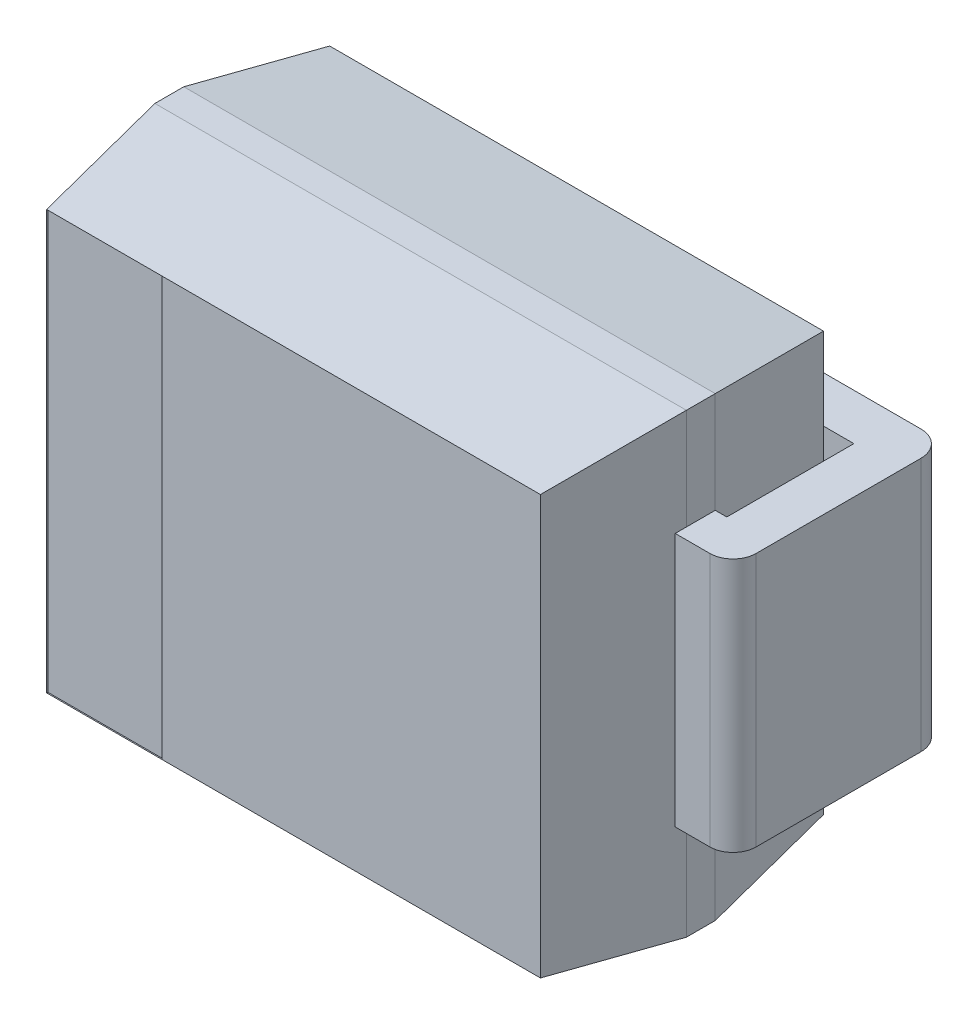
SolidWorks part; units mm, degrees
other "Детальный элемент1"
ref_plane "Спереди" through (0, 0, 0) normal (0, 0, 1) x (1, 0, 0)
ref_plane "Сверху" through (0, 0, 0) normal (0, 1, 0) x (1, 0, 0)
ref_plane "Справа" through (0, 0, 0) normal (1, 0, 0) x (0, 0, -1)
ref_plane "Плоскость1" through (0, 0, 0.4) normal (0, 0, 1) x (1, 0, 0)
sketch "Эскиз1" plane through (0, 0, 0.4) normal (0, 0, 1) x (1, 0, 0)
  line L1 (-2.3, 1.975) -> (2.3, 1.975)
  line L2 (-2.3, 1.975) -> (-2.3, -1.975)
  line L3 (-2.3, -1.975) -> (2.3, -1.975)
  line L4 (2.3, 1.975) -> (2.3, -1.975)
  line L5 (-2.3, 1.975) -> (2.3, -1.975) construction
  line L6 (-2.3, -1.975) -> (2.3, 1.975) construction
  point P0 (0, 0)
  dimension "D1" = 4.6
  dimension "D2" = 3.95
extrude "Бобышка-Вытянуть1" add sketch "Эскиз1" along normal blind 2.45
chamfer "Фаска1" distance 1.1 distance2 0.163 4 edges at (0, 1.975, 2.85) (2.3, 0, 2.85) (0, -1.975, 2.85) (-2.3, 0, 2.85)
chamfer "Фаска2" distance 0.163 distance2 1.1 4 edges at (2.3, 0, 0.4) (0, 1.975, 0.4) (0, -1.975, 0.4) (-2.3, 0, 0.4)
sketch "Эскиз2" plane through (0, 0, 0) normal (0, 1, 0) x (1, 0, 0)
  line L0 (-2.4, -0.4) -> (-2.4, -1.5)
  line L1 (-1.3, 0) -> (-2.58, 0)
  line L2 (-1.3, 0) -> (-1.3, -0.4)
  line L3 (-1.3, -0.4) -> (-2.4, -0.4)
  line L5 (-2.8, -1.6464) -> (-2.8, -0.22)
  line L6 (-2.6, -1.8464) -> (-2.3, -1.8464)
  line L7 (-2.3, -1.8464) -> (-2.3, -1.5)
  line L8 (-2.3, -1.5) -> (-2.4, -1.5)
  arc A2 (-2.6, -1.8464) -> (-2.8, -1.6464) centre (-2.6, -1.6464) cw
  arc A3 (-2.58, 0) -> (-2.8, -0.22) centre (-2.58, -0.22) ccw
  point P4 (0, 0)
  dimension "D3" = 0.22
  dimension "D6" = 0.2
  dimension "D1" = 0.4
  dimension "D2" = 0.4
  dimension "D4" = 1.5
  dimension "D5" = 0.5
extrude "Бобышка-Вытянуть2" add sketch "Эскиз2" along normal blind 1.1 and the other way blind 1.1 separate body
mirror "Зеркальное отражение1" about plane through (0, 0, 0) normal (1, 0, 0) of bodies 108
sketch "Эскиз3" plane through (0, 0, 2.85) normal (0, 0, 1) x (1, 0, 0)
  line L0 (2.137, 1.812) -> (-2.137, 1.812) construction
  line L1 (-2.137, -1.812) -> (-1.137, -1.812)
  line L2 (-2.137, -1.812) -> (-2.137, 1.812)
  line L3 (-2.137, 1.812) -> (-1.137, 1.812)
  line L4 (-1.137, -1.812) -> (-1.137, 1.812)
  dimension "D1" = 1
extrude "Вырез-Вытянуть1" cut sketch "Эскиз3" against normal blind 0.01
